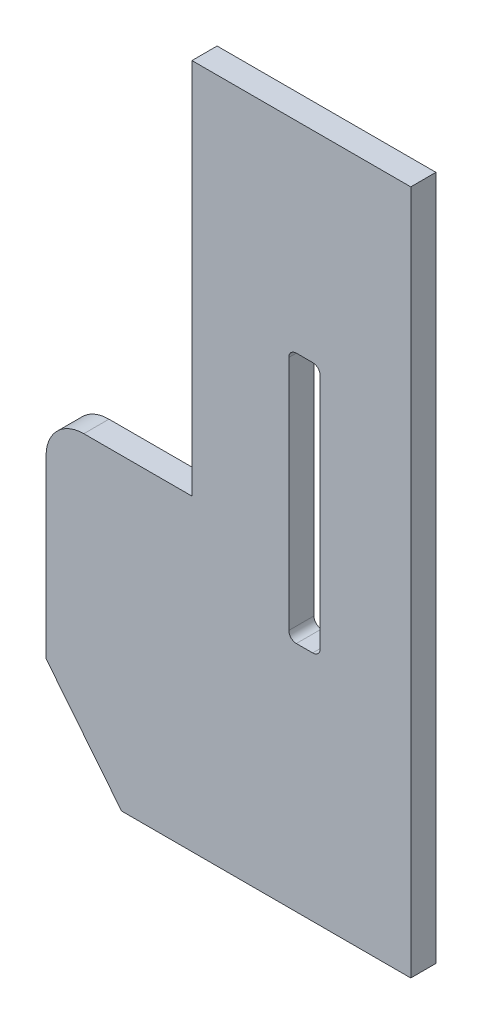
SolidWorks part; units mm, degrees
ref_plane "前视基准面" through (0, 0, 0) normal (0, 0, 1) x (1, 0, 0)
ref_plane "上视基准面" through (0, 0, 0) normal (0, 1, 0) x (1, 0, 0)
ref_plane "右视基准面" through (0, 0, 0) normal (1, 0, 0) x (0, 0, -1)
other "Configuration Table"
sketch "草图1" plane through (0, 0, 0) normal (0, 0, 1) x (1, 0, 0)
  line L0 (0, 0) -> (0, 50000) construction
  line L1 (0, 0) -> (50000, 0) construction
  line L3 (-72.5, 136.2175) -> (72.5, 136.2175)
  line L4 (-72.5, 136.2175) -> (-72.5, -136.2175)
  line L5 (-72.5, -136.2175) -> (72.5, -136.2175)
  line L6 (72.5, 136.2175) -> (72.5, -136.2175)
extrude "凸台-拉伸1" add sketch "草图1" along normal blind 10 contours L4 L3 L6 L5
sketch "草图2" plane through (0, 0, 0) normal (0, 0, 1) x (1, 0, 0)
  line L0 (0, 0) -> (0, 50000) construction
  line L1 (0, 0) -> (50000, 0) construction
  line L2 (-72.5, 136.2175) -> (72.5, 136.2175) construction
  line L3 (24, 56.2175) -> (36.5, 56.2175)
  line L4 (24, 56.2175) -> (24, -43.7825)
  line L5 (24, -43.7825) -> (36.5, -43.7825)
  line L6 (36.5, 56.2175) -> (36.5, -43.7825)
  line L7 (72.5, 136.2175) -> (72.5, -136.2175) construction
  line L8 (-14.5, 136.2175) -> (-14.5, -13.7825)
  line L9 (-14.5, -13.7825) -> (-72.5, -13.7825)
  line L10 (-72.5, 136.2175) -> (-72.5, -136.2175) construction
  line L11 (-72.5, -13.7825) -> (-72.5, -98.7825)
  line L12 (72.5, -136.2175) -> (-42.5, -136.2175)
  line L13 (-72.5, -136.2175) -> (72.5, -136.2175) construction
  line L14 (-72.5, -98.7825) -> (-42.5, -136.2175)
  line L15 (-14.5, 136.2175) -> (-72.5, 136.2175)
  line L16 (-72.5, 136.2175) -> (-72.5, -13.7825)
  line L17 (-72.5, -98.7825) -> (-72.5, -136.2175)
  line L18 (-72.5, 136.2175) -> (-72.5, -136.2175) construction
  line L19 (-72.5, -136.2175) -> (-42.5, -136.2175)
  dimension "D1" = 12.5
  dimension "D2" = 100
  dimension "D3" = 80
  dimension "D4" = 36
  dimension "D5" = 87
extrude "切除-拉伸1" cut sketch "草图2" along normal blind 10 contours L15 L16 L9 L8 | L17 L19 L14 | L6 L3 L4 L5
fillet "圆角1" radius 15 1 edges at (-72.5, -13.7825, 5)
fillet "圆角2" radius 3 4 edges at (36.5, -43.7825, 5) (24, -43.7825, 5) (24, 56.2175, 5) (36.5, 56.2175, 5)
